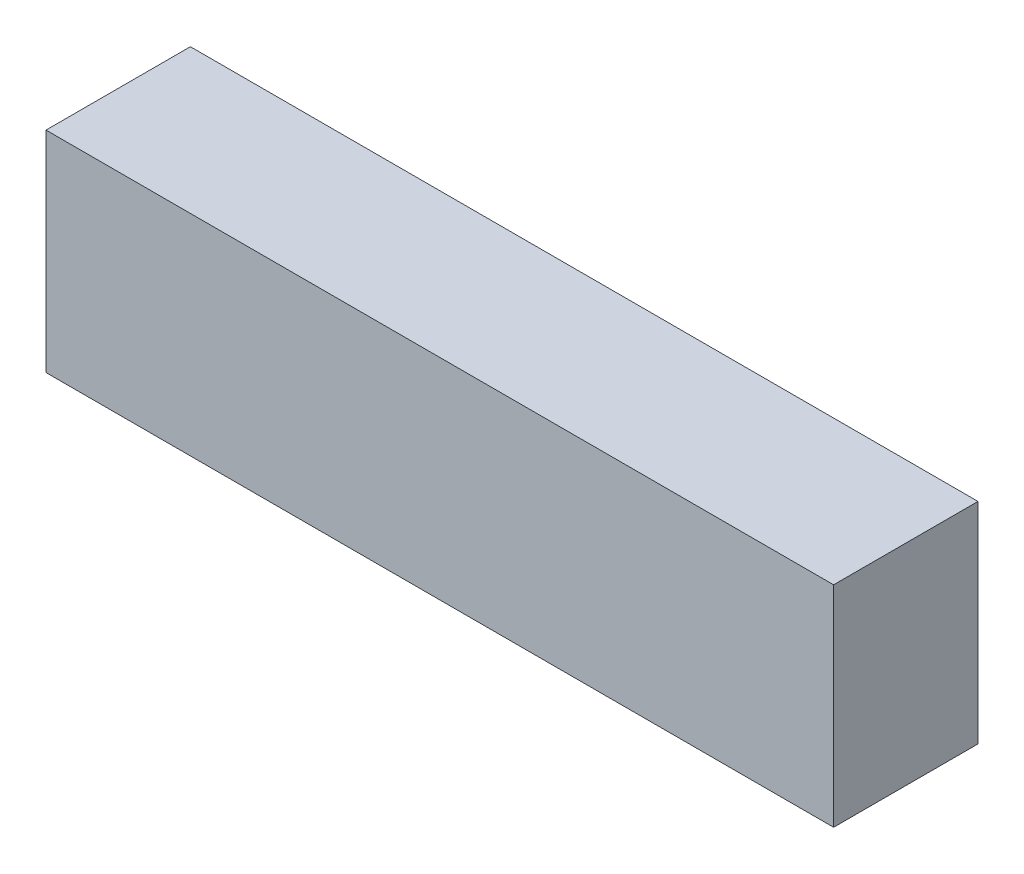
SolidWorks part; units mm, degrees
ref_plane "前视基准面" through (0, 0, 0) normal (0, 0, 1) x (1, 0, 0)
ref_plane "上视基准面" through (0, 0, 0) normal (0, 1, 0) x (1, 0, 0)
ref_plane "右视基准面" through (0, 0, 0) normal (1, 0, 0) x (0, 0, -1)
other "Configuration Table"
sketch "草图1" plane through (0, 0, 0) normal (0, 1, 0) x (1, 0, 0)
  line L1 (15, -2.75) -> (-15, -2.75)
  line L2 (15, -2.75) -> (15, 2.75)
  line L3 (15, 2.75) -> (-15, 2.75)
  line L4 (-15, -2.75) -> (-15, 2.75)
  line L5 (15, -2.75) -> (-15, 2.75) construction
  line L6 (15, 2.75) -> (-15, -2.75) construction
  point P0 (0, 0)
  dimension "D1" = 30
  dimension "D2" = 5.5
extrude "凸台-拉伸1" add sketch "草图1" along normal blind 8
